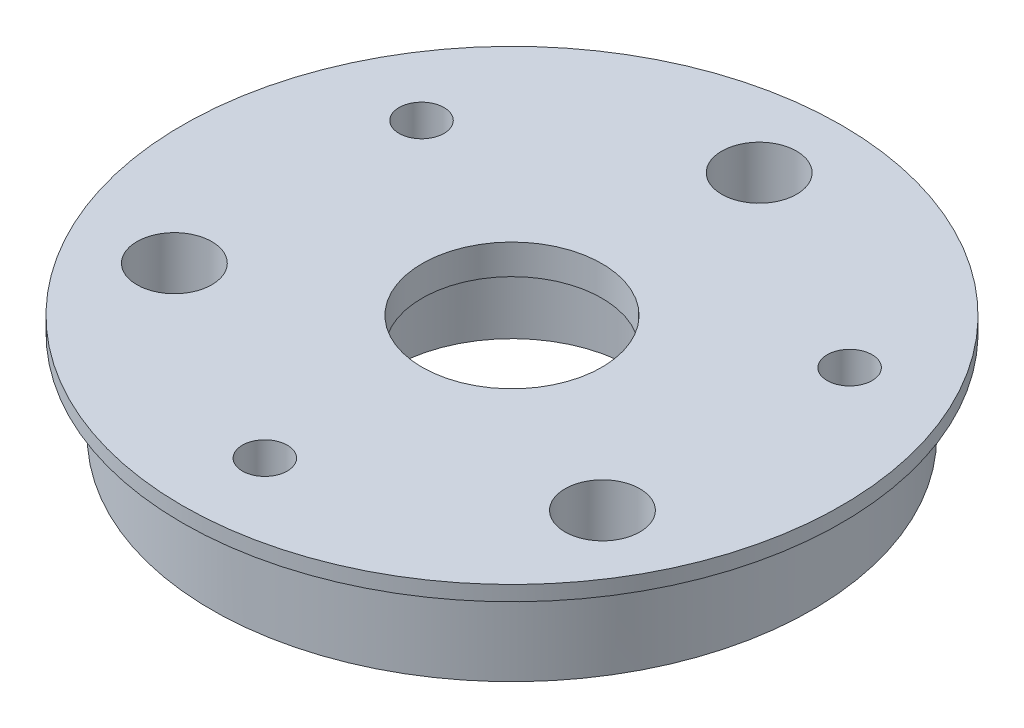
SolidWorks part; units mm, degrees
ref_plane "Front Plane" through (0, 0, 0) normal (0, 0, 1) x (1, 0, 0)
ref_plane "Top Plane" through (0, 0, 0) normal (0, 1, 0) x (1, 0, 0)
ref_plane "Right Plane" through (0, 0, 0) normal (1, 0, 0) x (0, 0, -1)
sketch "Sketch1" plane through (0, 0, 0) normal (0, 1, 0) x (1, 0, 0)
  circle A0 centre (0, 0) radius 20.05
  circle A1 centre (0, 0) radius 8
  dimension "D1" = 40.1
  dimension "D2" = 16
extrude "Boss-Extrude1" add sketch "Sketch1" along normal blind 8 contours A0 A1
sketch "Sketch2" plane through (0, 8, 0) normal (0, 1, 0) x (1, 0, 0)
  circle A0 centre (0, 0) radius 20
  circle A1 centre (0, 0) radius 20.05
  circle A2 centre (0, 0) radius 20.05
  circle M3 centre (0, 0) radius 8
  circle M4 centre (0, 0) radius 20.05
  dimension "D2" = 40
  dimension "D1" = 0
extrude "Boss-Extrude2" add sketch "Sketch2" along normal blind 7 contours M4 M3 | A0 M4
sketch "Sketch3" plane through (0, 15, 0) normal (0, 1, 0) x (1, 0, 0)
  circle A0 centre (0, 0) radius 8 construction
  circle A1 centre (0, 0) radius 8
  circle A2 centre (0, 0) radius 6
  dimension "D1" = 12
extrude "Boss-Extrude3" add sketch "Sketch3" against normal blind 2
sketch "Sketch4" plane through (0, 15, 0) normal (0, 1, 0) x (1, 0, 0)
  circle A0 centre (0, 0) radius 16.5 construction
  circle A1 centre (0, 16.5) radius 2.5
  circle A2 centre (14.2894, -8.25) radius 2.5
  circle A3 centre (-14.2894, -8.25) radius 2.5
  circle A4 centre (0, -16.5) radius 1.5
  circle A5 centre (-14.2894, 8.25) radius 1.5
  circle A6 centre (0, 0) radius 16.5 construction
  circle A7 centre (14.2894, 8.25) radius 1.5
  circle A8 centre (0, 0) radius 16.5 construction
  point P12 (0, 0)
  point P20 (0, 0)
  dimension "D1" = 33
  dimension "D2" = 5
  dimension "D4" = 3
  dimension "D3" = 3
  dimension "D5" = 3
extrude "Cut-Extrude1" cut sketch "Sketch4" against normal through all
sketch "Sketch5" plane through (0, 0, 0) normal (0, -1, 0) x (1, 0, 0)
  line L0 (-2.4973, 7.6002) -> (-6.2589, 19.0481)
  line L1 (0, 8) -> (0, 26.8969) construction
  line L2 (2.4973, 7.6002) -> (6.2589, 19.0481)
  line L3 (6.2589, 19.0481) -> (8.3676, 25.4658) construction
  line L4 (-6.2589, 19.0481) -> (-8.3676, 25.4658) construction
  line L5 (0, 0) -> (-2.4973, 7.6002) construction
  line L6 (0, 0) -> (0, 8) construction
  line L7 (0, 0) -> (2.4973, 7.6002) construction
  line L8 (0, 0) -> (-29.1337, -6.0918)
  circle A0 centre (-14.2894, 8.25) radius 2.5 construction
  circle A1 centre (-14.2894, 8.25) radius 2.5
  arc A2 (-20.0175, -1.1409) -> (-3.8391, 11.6838) centre (-14.2894, 8.25) ccw construction
  circle A3 centre (0, 0) radius 8 construction
  circle A4 centre (0, 0) radius 20.05 construction
  arc A5 (2.4973, 7.6002) -> (-2.4973, 7.6002) centre (0, 0) ccw
  arc A6 (6.2589, 19.0481) -> (-6.2589, 19.0481) centre (0, 0) ccw
  arc A7 (-7.9648, -0.7499) -> (2.4973, 7.6002) centre (0, 0) ccw
  arc A8 (-20.0175, -1.1409) -> (6.2589, 19.0481) centre (0, 0) ccw
  arc A9 (-3.3329, 7.2727) -> (-7.9648, -0.7499) centre (0, 0) ccw
  arc A10 (-2.4973, 7.6002) -> (-3.3329, 7.2727) centre (0, 0) ccw
  arc A11 (-3.8391, 11.6838) -> (-9.0207, 17.9061) centre (-14.2894, 8.25) ccw construction
  arc A12 (-6.2589, 19.0481) -> (-9.0207, 17.9061) centre (0, 0) ccw
  arc A13 (-9.0207, 17.9061) -> (-20.0175, -1.1409) centre (0, 0) ccw
  arc A14 (-9.0207, 17.9061) -> (-20.0175, -1.1409) centre (-14.2894, 8.25) ccw construction
  circle M7 centre (-14.2894, 8.25) radius 2.5
  circle M10 centre (0, 0) radius 8
  circle M11 centre (0, 0) radius 20.05
  dimension "D1" = 22
extrude "Cut-Extrude2" cut sketch "Sketch5" against normal blind 8 contours L8 L0 M10 M11 M7
pattern_circular "CirPattern1" count 3 over 360 about axis through (0, 0, 0) along (0, 1, 0) of "Cut-Extrude2"
fillet "Fillet1" radius 2 12 edges at (-6.2589, 4, 19.0481) (-7.8306, 4, -1.6374) (-19.6256, 4, -4.1037) (-13.3667, 4, -14.9444) (-5.3333, 4, -5.9628) (5.3333, 4, -5.9628) (13.3667, 4, -14.9444) (19.6256, 4, -4.1037) (7.8306, 4, -1.6374) (2.4973, 4, 7.6002) (6.2589, 4, 19.0481) (-2.4973, 4, 7.6002)
sketch "Sketch6" plane through (0, 15, 0) normal (0, 1, 0) x (1, 0, 0)
  circle A0 centre (0, 0) radius 20.05 construction
  circle A1 centre (0, 0) radius 20.05
  circle A2 centre (0, 0) radius 22
  dimension "D1" = 44
extrude "Boss-Extrude4" add sketch "Sketch6" against normal blind 1
sketch "Sketch7" plane through (0, 8, 0) normal (0, -1, 0) x (1, 0, 0)
  circle A0 centre (0, 0) radius 20.05 construction
  circle A1 centre (0, 0) radius 8 construction
  arc A2 (7.345, -3.1704) -> (0.9268, 7.9461) centre (0, 0) ccw construction
  arc A3 (19.05, -6.253) -> (4.1098, 19.6243) centre (0, 0) ccw construction
  circle A4 centre (0, 0) radius 20.05
  circle A5 centre (0, 0) radius 8
  arc A6 (7.345, -3.1704) -> (0.9268, 7.9461) centre (0, 0) ccw
  arc A7 (19.05, -6.253) -> (4.1098, 19.6243) centre (0, 0) ccw
  line M1 (5.5999, 17.0424) -> (3.0586, 9.3083)
  arc M2 (3.0586, 9.3083) -> (0.9268, 7.9461) centre (1.1585, 9.9327) cw
  arc M3 (0.9268, 7.9461) -> (7.345, -3.1704) centre (0, 0) cw
  arc M4 (7.345, -3.1704) -> (9.5905, -2.0054) centre (9.1812, -3.963) cw
  line M5 (9.5905, -2.0054) -> (17.5591, -3.6716)
  arc M6 (17.5591, -3.6716) -> (19.05, -6.253) centre (17.1498, -5.6292) cw
  arc M7 (19.05, -6.253) -> (4.1098, 19.6243) centre (0, 0) ccw
  arc M8 (4.1098, 19.6243) -> (5.5999, 17.0424) centre (3.6998, 17.6667) cw
  circle M9 centre (14.2894, 8.25) radius 2.5
extrude "Cut-Extrude3" cut sketch "Sketch7" along normal through all contours M8 M1 M2 M3 M4 M5 M6 M7 M9 | A5 A4 M2 M1 M8 M6 M5 M4
